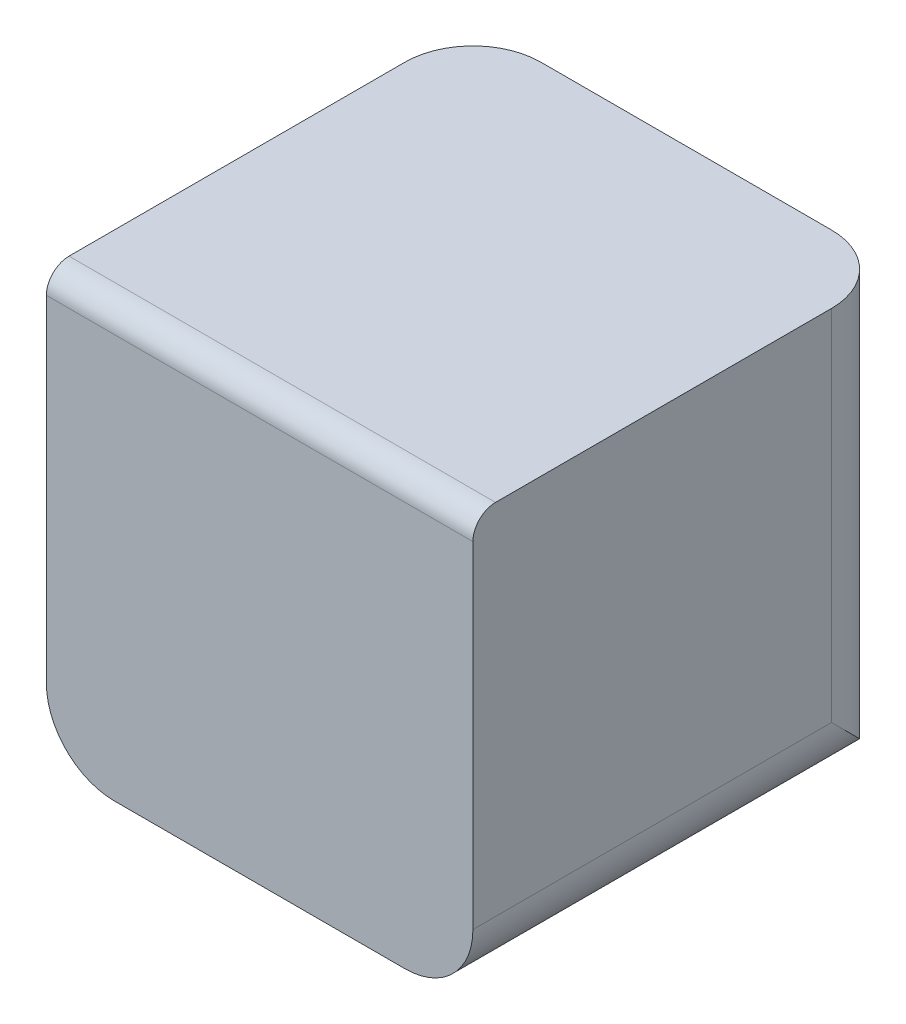
SolidWorks part; units mm, degrees
ref_plane "前视基准面" through (0, 0, 0) normal (0, 0, 1) x (1, 0, 0)
ref_plane "上视基准面" through (0, 0, 0) normal (0, 1, 0) x (1, 0, 0)
ref_plane "右视基准面" through (0, 0, 0) normal (1, 0, 0) x (0, 0, -1)
sketch "草图1" plane through (0, 0, 0) normal (0, 1, 0) x (1, 0, 0)
  line L1 (-9.42, -9.42) -> (9.42, -9.42)
  line L2 (-9.42, -9.42) -> (-9.42, 9.42)
  line L3 (-9.42, 9.42) -> (9.42, 9.42)
  line L4 (9.42, -9.42) -> (9.42, 9.42)
  line L5 (0, 9.42) -> (0, -9.42) construction
  line L6 (-9.42, 0) -> (9.42, 0) construction
  point P0 (0, 0)
  dimension "D1" = 18.84
  dimension "D2" = 18.84
extrude "凸台-拉伸1" add sketch "草图1" along normal blind 18.84
fillet "圆角1" radius 1 1 edges at (0, 18.84, 9.42)
fillet "圆角2" radius 3 4 edges at (9.42, 9.42, -9.42) (-9.42, 9.42, -9.42) (-9.42, 0, 0) (9.42, 0, 0)
